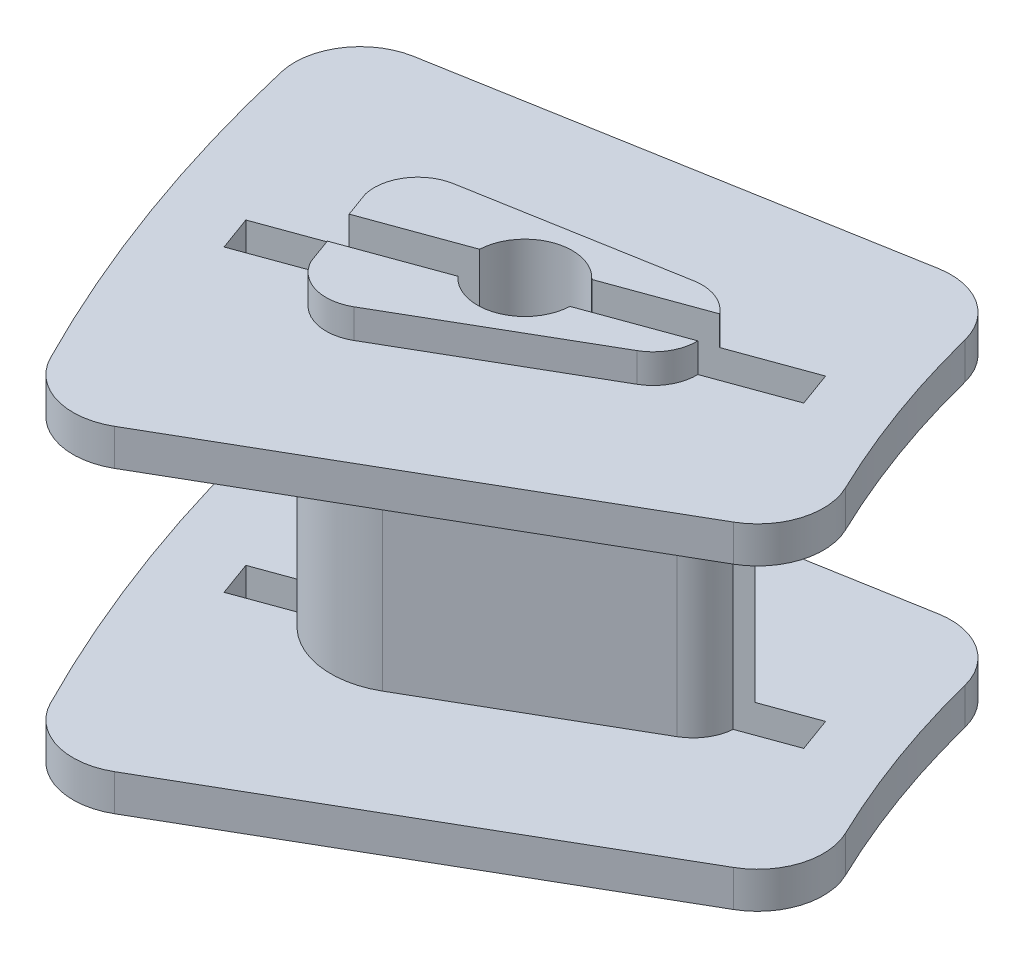
SolidWorks part; units mm, degrees
ref_plane "Front Plane" through (0, 0, 0) normal (0, 0, 1) x (1, 0, 0)
ref_plane "Top Plane" through (0, 0, 0) normal (0, 1, 0) x (1, 0, 0)
ref_plane "Right Plane" through (0, 0, 0) normal (1, 0, 0) x (0, 0, -1)
sketch "Sketch1" plane through (0, 0, 0) normal (0, 1, 0) x (1, 0, 0)
  line L0 (-0.3002, 0.1873) -> (-121.6087, -43.9654) construction
  line L1 (-0.3002, 0.1873) -> (-143.1552, -25.0019) construction
  line L2 (-0.3002, 0.1873) -> (-112.4354, -64.554) construction
  line L3 (-72.307, -13.5248) -> (-102.8964, -18.9186)
  line L4 (-64.2746, -35.5936) -> (-91.1745, -51.1242)
  line L5 (-2.7034, 0) -> (2.5073, 0) construction
  line L6 (0, 2.0352) -> (0, -1.7517) construction
  arc A0 (-97.4346, -49.2689) -> (-106.4993, -24.3638) centre (-0.3002, 0.1873) cw
  arc A1 (-72.307, -13.5248) -> (-67.1649, -16.8456) centre (-71.5256, -17.9565) cw
  arc A2 (-67.1649, -16.8456) -> (-62.4701, -29.7444) centre (-0.3002, 0.1873) ccw
  arc A3 (-62.4701, -29.7444) -> (-64.2746, -35.5936) centre (-66.5246, -31.6965) cw
  arc A4 (-97.4346, -49.2689) -> (-91.1745, -51.1242) centre (-93.4245, -47.2271) ccw
  arc A5 (-106.4993, -24.3638) -> (-102.8964, -18.9186) centre (-102.1149, -23.3502) cw
  dimension "D2" = 109
  dimension "D3" = 69
  dimension "D4" = 4.5
  dimension "D1" = 10
  dimension "D5" = 20
  dimension "D6" = 10
  dimension "D7" = 10
extrude "Boss-Extrude1" add sketch "Sketch1" along normal blind 2.5
sketch "Sketch2" plane through (0, 2.5, 0) normal (0, 1, 0) x (1, 0, 0)
  line L0 (-65.139, -23.4121) -> (-102.7267, -37.0929) construction
  line L1 (-75.6696, -26.6415) -> (-75.2938, -27.6739) construction
  line L4 (-75.9966, -24.2199) -> (-90.5443, -26.785)
  line L5 (-73.9756, -29.7724) -> (-86.7687, -37.1584)
  line L6 (-90.3897, -30.0554) -> (-88.7702, -34.5049) construction
  line L7 (-86.4226, -23.4121) -> (-80.5385, -39.5785) construction
  line L8 (-72.307, -13.5248) -> (-102.8964, -18.9186) construction
  arc A0 (-67.1649, -16.8456) -> (-62.4701, -29.7444) centre (-0.3002, 0.1873) ccw construction
  arc A1 (-106.4993, -24.3638) -> (-97.4346, -49.2689) centre (-0.3002, 0.1873) ccw construction
  arc A5 (-90.5443, -26.785) -> (-86.7687, -37.1584) centre (-89.571, -32.3046) ccw
  arc A6 (-73.9756, -29.7724) -> (-75.9966, -24.2199) centre (-75.4756, -27.1743) ccw
  point P17 (-83.9329, -30.2525)
  point P21 (-94.8378, -34.2215)
  point P22 (-72.6566, -26.1482)
  point P23 (-102.7267, -37.0929)
  point P25 (-65.139, -23.4121)
  dimension "D1" = 3
  dimension "D3" = 6
  dimension "D4" = 9
  dimension "D5" = 8
  dimension "D6" = 8.3953
extrude "Boss-Extrude2" add sketch "Sketch2" along normal blind 18
ref_plane "Plane1" through (0, 11.5, 0) normal (0, 1, 0) x (1, 0, 0)
mirror "Mirror1" about plane through (0, 11.5, 0) normal (0, 1, 0) of "Boss-Extrude1"
sketch "Sketch4" plane through (0, 23, 0) normal (0, 1, 0) x (1, 0, 0)
  line L0 (-65.139, -23.4121) -> (-102.7267, -37.0929) construction
  line L1 (-83.5264, -31.3692) -> (-84.4236, -28.9042) construction
  line L2 (-98.9256, -34.3792) -> (-87.1795, -30.1039)
  line L3 (-69.7952, -23.7765) -> (-81.5413, -28.0518)
  line L4 (-98.0706, -36.7284) -> (-86.3244, -32.4531)
  line L5 (-68.9401, -26.1258) -> (-80.6863, -30.401)
  line L6 (-98.9256, -34.3792) -> (-98.0706, -36.7284)
  line L7 (-69.7952, -23.7765) -> (-68.9401, -26.1258)
  arc A0 (-86.3244, -32.4531) -> (-80.6863, -30.401) centre (-83.9329, -30.2525) ccw
  arc A1 (-67.1649, -16.8456) -> (-62.4701, -29.7444) centre (-0.3002, 0.1873) ccw construction
  arc A2 (-106.4993, -24.3638) -> (-97.4346, -49.2689) centre (-0.3002, 0.1873) ccw construction
  arc A3 (-81.5413, -28.0518) -> (-87.1795, -30.1039) centre (-83.9329, -30.2525) ccw
  point P10 (-83.9329, -30.2525)
  point P13 (-102.7267, -37.0929)
  dimension "D1" = 6.5
  dimension "D2" = 12.5
  dimension "D3" = 2.5
extrude "Cut-Extrude1" cut sketch "Sketch4" against normal through all
sketch "Sketch5" plane through (0, 23, 0) normal (0, 1, 0) x (1, 0, 0)
  line L0 (-88.0702, -37.8288) -> (-75.7588, -30.7209)
  line L1 (-77.9722, -24.6395) -> (-91.9722, -27.108)
  line L6 (-102.7267, -37.0929) -> (-65.139, -23.4121) construction
  line L8 (-94.3765, -30.7281) -> (-93.7352, -32.49)
  line L9 (-77.6528, -27.0403) -> (-77.052, -28.691) construction
  line L10 (-89.2596, -36.084) -> (-91.7507, -29.2397) construction
  line L15 (-80.6863, -30.401) -> (-68.9401, -26.1258) construction
  line L16 (-69.7952, -23.7765) -> (-81.5413, -28.0518) construction
  line L21 (-80.6863, -30.401) -> (-74.2594, -28.0618)
  line L22 (-75.1144, -25.7126) -> (-81.5413, -28.0518)
  line L23 (-93.7352, -32.49) -> (-93.3077, -33.6646) construction
  line L24 (-92.8802, -34.8392) -> (-92.2389, -36.6012)
  line L25 (-93.3077, -33.6646) -> (-92.8802, -34.8392) construction
  line L26 (-69.7952, -23.7765) -> (-75.1144, -25.7126) construction
  line L28 (-74.2594, -28.0618) -> (-68.9401, -26.1258) construction
  line L29 (-92.8802, -34.8392) -> (-86.3244, -32.4531)
  line L30 (-93.7352, -32.49) -> (-87.1795, -30.1039)
  arc A18 (-106.4993, -24.3638) -> (-97.4346, -49.2689) centre (-0.3002, 0.1873) ccw construction
  arc A19 (-67.1649, -16.8456) -> (-62.4701, -29.7444) centre (-0.3002, 0.1873) ccw construction
  arc A20 (-75.1144, -25.7126) -> (-77.9722, -24.6395) centre (-77.4513, -27.5939) ccw
  arc A21 (-74.2594, -28.0618) -> (-75.7588, -30.7209) centre (-77.2588, -28.1228) cw
  arc A22 (-88.0702, -37.8288) -> (-92.2389, -36.6012) centre (-89.5702, -35.2308) cw
  arc A23 (-94.3765, -30.7281) -> (-91.9722, -27.108) centre (-91.4513, -30.0625) cw
  arc A24 (-86.3244, -32.4531) -> (-80.6863, -30.401) centre (-83.9329, -30.2525) ccw construction
  arc A25 (-81.5413, -28.0518) -> (-87.1795, -30.1039) centre (-83.9329, -30.2525) ccw construction
  arc A26 (-86.3244, -32.4531) -> (-80.6863, -30.401) centre (-83.9329, -30.2525) ccw
  arc A27 (-81.5413, -28.0518) -> (-87.1795, -30.1039) centre (-83.9329, -30.2525) ccw
  dimension "D2" = 3
  dimension "D1" = 10
  dimension "D3" = 5.5
  dimension "D4" = 14
  dimension "D5" = 6.25
  dimension "D8" = 10.0235
extrude "Boss-Extrude3" add sketch "Sketch5" along normal blind 2
